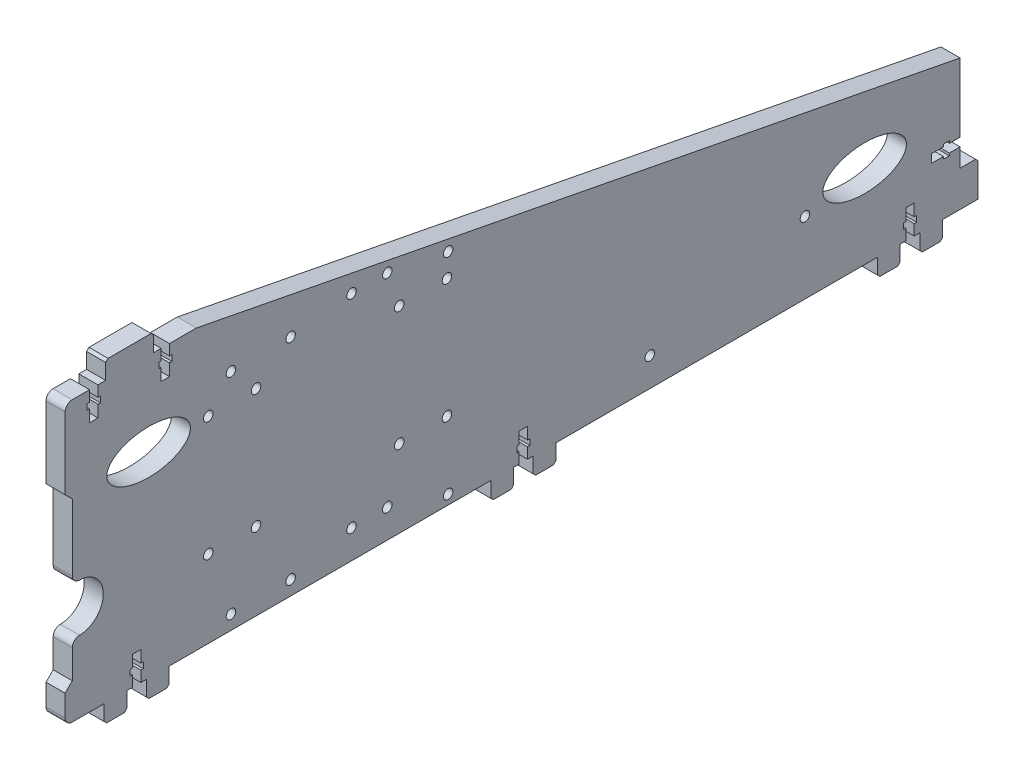
SolidWorks part; units mm, degrees
ref_plane "Front Plane" through (0, 0, 0) normal (0, 0, 1) x (1, 0, 0)
ref_plane "Top Plane" through (0, 0, 0) normal (0, 1, 0) x (1, 0, 0)
ref_plane "Right Plane" through (0, 0, 0) normal (1, 0, 0) x (0, 0, -1)
sketch "Sketch1" plane through (0, 0, 0) normal (1, 0, 0) x (0, 0, -1)
  line L0 (377.0111, 9.4389) -> (384.5111, 9.4389)
  line L1 (384.5111, 9.4389) -> (384.5111, 24.4389)
  line L2 (384.5111, 24.4389) -> (377.0111, 24.4389)
  line L3 (377.0111, 24.4389) -> (377.0111, 32.1889)
  line L4 (377.0111, 32.1889) -> (372.5111, 32.1889)
  line L5 (372.5111, 32.1889) -> (372.5111, 31.1889)
  line L6 (372.5111, 31.1889) -> (370.0111, 31.1889)
  line L7 (370.0111, 31.1889) -> (370.0111, 32.1889)
  line L8 (370.0111, 32.1889) -> (365.0111, 32.1889)
  line L9 (365.0111, 32.1889) -> (365.0111, 35.6889)
  line L10 (365.0111, 35.6889) -> (370.0111, 35.6889)
  line L11 (370.0111, 35.6889) -> (370.0111, 36.6889)
  line L12 (370.0111, 36.6889) -> (372.5111, 36.6889)
  line L13 (372.5111, 36.6889) -> (372.5111, 35.6889)
  line L14 (372.5111, 35.6889) -> (377.0111, 35.6889)
  line L15 (377.0111, 35.6889) -> (377.0111, 64.4389)
  line L16 (377.0111, 64.4389) -> (57.0111, 126.4389)
  line L17 (57.0111, 126.4389) -> (45.7611, 126.4389)
  line L18 (45.7611, 126.4389) -> (45.7611, 121.9389)
  line L19 (45.7611, 121.9389) -> (46.7611, 121.9389)
  line L20 (46.7611, 121.9389) -> (46.7611, 119.4389)
  line L21 (46.7611, 119.4389) -> (45.7611, 119.4389)
  line L22 (45.7611, 119.4389) -> (45.7611, 114.4389)
  line L23 (45.7611, 114.4389) -> (42.2611, 114.4389)
  line L24 (42.2611, 114.4389) -> (42.2611, 119.4389)
  line L25 (42.2611, 119.4389) -> (41.2611, 119.4389)
  line L26 (41.2611, 119.4389) -> (41.2611, 121.9389)
  line L27 (41.2611, 121.9389) -> (42.2611, 121.9389)
  line L28 (42.2611, 121.9389) -> (42.2611, 126.4389)
  line L29 (42.2611, 126.4389) -> (39.0111, 126.4389)
  line L30 (39.0111, 126.4389) -> (39.0111, 132.9389)
  line L31 (39.0111, 132.9389) -> (38.0111, 133.9389)
  line L32 (38.0111, 133.9389) -> (20.0111, 133.9389)
  line L33 (20.0111, 133.9389) -> (19.0111, 132.9389)
  line L34 (19.0111, 132.9389) -> (19.0111, 126.4389)
  line L35 (19.0111, 126.4389) -> (15.7611, 126.4389)
  line L36 (15.7611, 126.4389) -> (15.7611, 121.9389)
  line L37 (15.7611, 121.9389) -> (16.7611, 121.9389)
  line L38 (16.7611, 121.9389) -> (16.7611, 119.4389)
  line L39 (16.7611, 119.4389) -> (15.7611, 119.4389)
  line L40 (15.7611, 119.4389) -> (15.7611, 114.4389)
  line L41 (15.7611, 114.4389) -> (12.2611, 114.4389)
  line L42 (12.2611, 114.4389) -> (12.2611, 119.4389)
  line L43 (12.2611, 119.4389) -> (11.2611, 119.4389)
  line L44 (11.2611, 119.4389) -> (11.2611, 121.9389)
  line L45 (11.2611, 121.9389) -> (12.2611, 121.9389)
  line L46 (12.2611, 121.9389) -> (12.2611, 126.4389)
  line L47 (12.2611, 126.4389) -> (5.0111, 126.4389)
  line L48 (2.0111, 123.4389) -> (2.0111, 93.4389)
  line L49 (2.0111, 93.4389) -> (5.0111, 90.4389)
  line L50 (5.0111, 90.4389) -> (5.0111, 62.4389)
  line L51 (5.0111, 36.4389) -> (5.0111, 24.4389)
  line L52 (5.0111, 24.4389) -> (2.0111, 21.4389)
  line L53 (2.0111, 21.4389) -> (2.0111, 12.4389)
  line L54 (5.0111, 9.4389) -> (18.3861, 9.4389)
  line L55 (18.3861, 9.4389) -> (18.3861, 2.9389)
  line L56 (18.3861, 2.9389) -> (19.3861, 1.9389)
  line L57 (19.3861, 1.9389) -> (26.8861, 1.9389)
  line L58 (26.8861, 1.9389) -> (27.8861, 2.9389)
  line L59 (27.8861, 2.9389) -> (27.8861, 9.4389)
  line L60 (27.8861, 9.4389) -> (30.2611, 9.4389)
  line L61 (30.2611, 9.4389) -> (30.2611, 13.9389)
  line L62 (30.2611, 13.9389) -> (29.2611, 13.9389)
  line L63 (29.2611, 13.9389) -> (29.2611, 16.4389)
  line L64 (29.2611, 16.4389) -> (30.2611, 16.4389)
  line L65 (30.2611, 16.4389) -> (30.2611, 21.4389)
  line L66 (30.2611, 21.4389) -> (33.7611, 21.4389)
  line L67 (33.7611, 21.4389) -> (33.7611, 16.4389)
  line L68 (33.7611, 16.4389) -> (34.7611, 16.4389)
  line L69 (34.7611, 16.4389) -> (34.7611, 13.9389)
  line L70 (34.7611, 13.9389) -> (33.7611, 13.9389)
  line L71 (33.7611, 13.9389) -> (33.7611, 9.4389)
  line L72 (33.7611, 9.4389) -> (36.1361, 9.4389)
  line L73 (36.1361, 9.4389) -> (36.1361, 2.9389)
  line L74 (36.1361, 2.9389) -> (37.1361, 1.9389)
  line L75 (37.1361, 1.9389) -> (44.6361, 1.9389)
  line L76 (44.6361, 1.9389) -> (45.6361, 2.9389)
  line L77 (45.6361, 2.9389) -> (45.6361, 9.4389)
  line L78 (45.6361, 9.4389) -> (180.3861, 9.4389)
  line L79 (180.3861, 9.4389) -> (180.3861, 2.9389)
  line L80 (180.3861, 2.9389) -> (181.3861, 1.9389)
  line L81 (181.3861, 1.9389) -> (188.8861, 1.9389)
  line L82 (188.8861, 1.9389) -> (189.8861, 2.9389)
  line L83 (189.8861, 2.9389) -> (189.8861, 9.4389)
  line L84 (189.8861, 9.4389) -> (192.2611, 9.4389)
  line L85 (192.2611, 9.4389) -> (192.2611, 13.9389)
  line L86 (192.2611, 13.9389) -> (191.2611, 13.9389)
  line L87 (191.2611, 13.9389) -> (191.2611, 16.4389)
  line L88 (191.2611, 16.4389) -> (192.2611, 16.4389)
  line L89 (192.2611, 16.4389) -> (192.2611, 21.4389)
  line L90 (192.2611, 21.4389) -> (195.7611, 21.4389)
  line L91 (195.7611, 21.4389) -> (195.7611, 16.4389)
  line L92 (195.7611, 16.4389) -> (196.7611, 16.4389)
  line L93 (196.7611, 16.4389) -> (196.7611, 13.9389)
  line L94 (196.7611, 13.9389) -> (195.7611, 13.9389)
  line L95 (195.7611, 13.9389) -> (195.7611, 9.4389)
  line L96 (195.7611, 9.4389) -> (198.1361, 9.4389)
  line L97 (198.1361, 9.4389) -> (198.1361, 2.9389)
  line L98 (198.1361, 2.9389) -> (199.1361, 1.9389)
  line L99 (199.1361, 1.9389) -> (206.6361, 1.9389)
  line L100 (206.6361, 1.9389) -> (207.6361, 2.9389)
  line L101 (207.6361, 2.9389) -> (207.6361, 9.4389)
  line L102 (207.6361, 9.4389) -> (342.3861, 9.4389)
  line L103 (342.3861, 9.4389) -> (342.3861, 2.9389)
  line L104 (342.3861, 2.9389) -> (343.3861, 1.9389)
  line L105 (343.3861, 1.9389) -> (350.8861, 1.9389)
  line L106 (350.8861, 1.9389) -> (351.8861, 2.9389)
  line L107 (351.8861, 2.9389) -> (351.8861, 9.4389)
  line L108 (351.8861, 9.4389) -> (354.2611, 9.4389)
  line L109 (354.2611, 9.4389) -> (354.2611, 13.9389)
  line L110 (354.2611, 13.9389) -> (353.2611, 13.9389)
  line L111 (353.2611, 13.9389) -> (353.2611, 16.4389)
  line L112 (353.2611, 16.4389) -> (354.2611, 16.4389)
  line L113 (354.2611, 16.4389) -> (354.2611, 21.4389)
  line L114 (354.2611, 21.4389) -> (357.7611, 21.4389)
  line L115 (357.7611, 21.4389) -> (357.7611, 16.4389)
  line L116 (357.7611, 16.4389) -> (358.7611, 16.4389)
  line L117 (358.7611, 16.4389) -> (358.7611, 13.9389)
  line L118 (358.7611, 13.9389) -> (357.7611, 13.9389)
  line L119 (357.7611, 13.9389) -> (357.7611, 9.4389)
  line L120 (357.7611, 9.4389) -> (360.1361, 9.4389)
  line L121 (360.1361, 9.4389) -> (360.1361, 2.9389)
  line L122 (360.1361, 2.9389) -> (361.1361, 1.9389)
  line L123 (361.1361, 1.9389) -> (368.6361, 1.9389)
  line L124 (368.6361, 1.9389) -> (369.6361, 2.9389)
  line L125 (369.6361, 2.9389) -> (369.6361, 9.4389)
  line L126 (369.6361, 9.4389) -> (377.0111, 9.4389)
  arc A0 (5.0111, 126.4389) -> (2.0111, 123.4389) centre (5.0111, 123.4389) ccw
  arc A1 (5.0111, 62.4389) -> (8.0111, 59.4389) centre (8.0111, 62.4389) ccw
  arc A2 (8.0111, 39.4389) -> (8.0111, 59.4389) centre (8.0111, 49.4389) ccw
  arc A3 (8.0111, 39.4389) -> (5.0111, 36.4389) centre (8.0111, 36.4389) ccw
  arc A4 (2.0111, 12.4389) -> (5.0111, 9.4389) centre (5.0111, 12.4389) ccw
  circle A5 centre (71.5111, 15.4389) radius 2
  circle A6 centre (162.5111, 13.4389) radius 2
  circle A7 centre (71.5111, 103.4389) radius 2
  circle A8 centre (162.5111, 101.4389) radius 2
  circle A9 centre (122.0111, 21.4389) radius 2
  circle A10 centre (122.0111, 106.4389) radius 2
  circle A11 centre (247.0111, 21.4389) radius 2
  circle A12 centre (312.0111, 39.4389) radius 2
  ellipse E0 centre (337.0111, 44.4389) end of major axis (354.5111, 44.4389) minor radius 9.25
  ellipse E1 centre (37.0111, 91.4389) end of major axis (54.5111, 91.4389) minor radius 9.25
extrude "Extrude1" add sketch "Sketch1" along normal blind 8
sketch "Sketch2" plane through (0, 114.4389, 0) normal (0, 1, 0) x (1, 0, 0)
  line L0 (0, 45.7611) -> (8, 42.2611)
  circle A0 centre (4, 44.0111) radius 1
  dimension "D1" = 2
extrude "Extrude2" cut sketch "Sketch2" against normal blind 1 contours A0
sketch "Sketch3" plane through (0, 114.4389, 0) normal (0, 1, 0) x (1, 0, 0)
  line L0 (8, 15.7611) -> (0, 12.2611)
  circle A0 centre (4, 14.0111) radius 1
  dimension "D1" = 2
extrude "Extrude3" cut sketch "Sketch3" against normal blind 1 contours A0
sketch "Sketch4" plane through (0, 21.4389, 0) normal (0, -1, 0) x (1, 0, 0)
  line L0 (0, -30.2611) -> (8, -33.7611)
  circle A0 centre (4, -32.0111) radius 1
  dimension "D1" = 2
extrude "Extrude4" cut sketch "Sketch4" against normal blind 1 contours A0
sketch "Sketch5" plane through (0, 21.4389, 0) normal (0, -1, 0) x (1, 0, 0)
  line L0 (0, -357.7611) -> (8, -354.2611)
  circle A0 centre (4, -356.0111) radius 1
  dimension "D1" = 2
extrude "Extrude5" cut sketch "Sketch5" against normal blind 1 contours A0
sketch "Sketch6" plane through (0, 0, -365.0111) normal (0, 0, -1) x (-1, 0, 0)
  line L0 (-8, 35.6889) -> (0, 32.1889) construction
  circle A0 centre (-4, 33.9389) radius 1
  dimension "D1" = 2
extrude "Extrude6" cut sketch "Sketch6" against normal blind 1
chamfer "Chamfer1" distance 1 angle 45 1 edges at (4, 24.4389, -384.5111)
sketch "Sketch7" plane through (8, 0, 0) normal (1, 0, 0) x (0, 0, -1)
  line L0 (62.0111, 9.4389) -> (62.0111, 41.9389) construction
  line L1 (45.6361, 9.4389) -> (180.3861, 9.4389) construction
  line L2 (2.0111, 21.4389) -> (2.0111, 12.4389) construction
  line L3 (2.0111, 123.4389) -> (2.0111, 93.4389) construction
  line L4 (71.5111, 15.4389) -> (96.5111, 15.4389) construction
  line L5 (71.5111, 103.4389) -> (96.5111, 103.4389) construction
  line L6 (122.0111, 106.4389) -> (137.0111, 106.4389) construction
  line L7 (122.0111, 21.4389) -> (137.0111, 21.4389) construction
  circle A0 centre (62.0111, 41.9389) radius 2
  circle A1 centre (82.0111, 41.9389) radius 2
  circle A4 centre (142.0111, 41.9389) radius 2
  circle A5 centre (162.0111, 41.9389) radius 2
  circle A8 centre (82.0111, 91.9389) radius 2
  circle A11 centre (142.0111, 91.9389) radius 2
  circle A12 centre (162.0111, 91.9389) radius 2
  circle A15 centre (62.0111, 91.9389) radius 2
  circle A16 centre (102.0111, 91.9389) radius 2 [skipped]
  circle A17 centre (102.0111, 41.9389) radius 2 [skipped]
  circle A18 centre (122.0111, 91.9389) radius 2 [skipped]
  circle A19 centre (122.0111, 41.9389) radius 2 [skipped]
  circle A21 centre (96.5111, 103.4389) radius 2
  circle A22 centre (96.5111, 15.4389) radius 2
  circle A25 centre (137.0111, 21.4389) radius 2
  circle A26 centre (137.0111, 106.4389) radius 2
  point P6 (2.0111, 16.9389)
  dimension "D3" = 4
  dimension "D6" = 60
  dimension "D7" = 50
  dimension "D8" = 20
  dimension "D9" = 25
  dimension "D11" = 4
  dimension "D12" = 4
  dimension "D15" = 4
  dimension "D16" = 4
  dimension "D1" = 32.5
  dimension "D2" = 60
  dimension "D10" = 25
  dimension "D13" = 15
  dimension "D14" = 15
  dimension "D4" = 6
  dimension "D5" = 2
extrude "Cut-Extrude1" cut sketch "Sketch7" against normal through all
